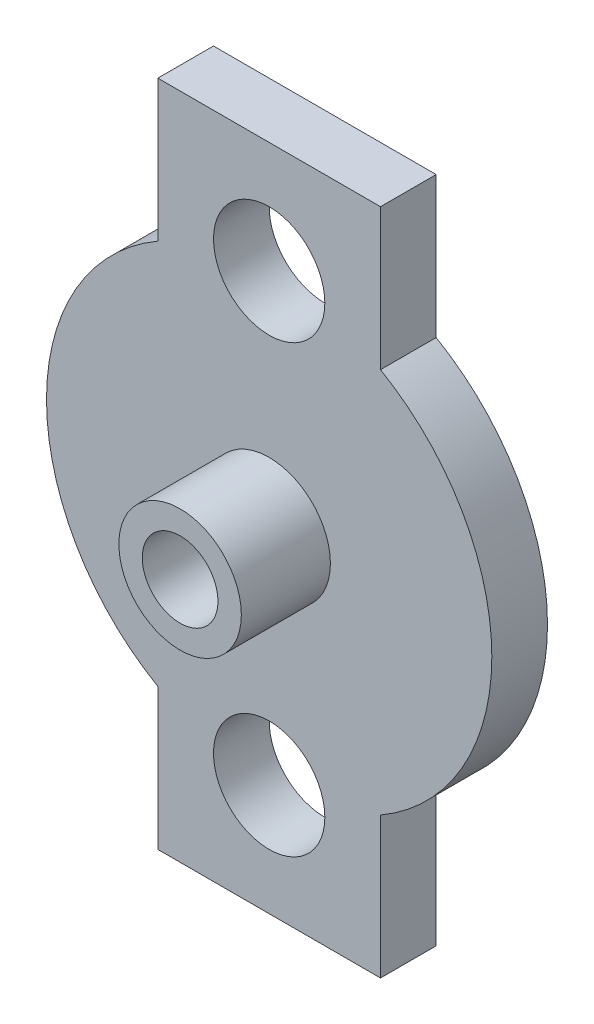
SolidWorks part; units mm, degrees
ref_plane "Plan de face" through (0, 0, 0) normal (0, 0, 1) x (1, 0, 0)
ref_plane "Plan de dessus" through (0, 0, 0) normal (0, 1, 0) x (1, 0, 0)
ref_plane "Plan de droite" through (0, 0, 0) normal (1, 0, 0) x (0, 0, -1)
sketch "Esquisse4" plane through (0, 0, 0) normal (0, 0, 1) x (1, 0, 0)
  circle A0 centre (0, 0) radius 10
  dimension "D1" = 20
extrude "Boss.-Extru.3" add sketch "Esquisse4" along normal blind 2.5
sketch "Esquisse5" plane through (0, 0, 2.5) normal (0, 0, 1) x (1, 0, 0)
  circle A0 centre (0, 0) radius 0.8
  dimension "D1" = 1.6
extrude "Enlèv. mat.-Extru.2" cut sketch "Esquisse5" against normal blind 3
sketch "Esquisse6" plane through (0, 0, 2.5) normal (0, 0, 1) x (1, 0, 0)
  circle A0 centre (0, 0) radius 1.7
  circle A1 centre (0, 0) radius 2.75
  dimension "D1" = 5.5
  dimension "D2" = 3.4
extrude "Boss.-Extru.4" add sketch "Esquisse6" along normal blind 4
sketch "Esquisse10" plane through (0, 0, 2.5) normal (0, 0, 1) x (1, 0, 0)
  circle A0 centre (0, 0) radius 1.7
  dimension "D1" = 3.4
extrude "Enlèv. mat.-Extru.3" cut sketch "Esquisse10" against normal blind 1
sketch "Esquisse17" plane through (0, 0, 2.5) normal (0, 0, 1) x (1, 0, 0)
  line L0 (-5, -8.6603) -> (-5, -15)
  line L1 (-5, -15) -> (5, -15)
  line L2 (5, -15) -> (5, -8.6603)
  line L4 (1.375, 0) -> (-1.375, 0) construction
  line L5 (5, 15) -> (5, 8.6603)
  line L6 (-5, 15) -> (5, 15)
  line L7 (-5, 8.6603) -> (-5, 15)
  circle A0 centre (0, 0) radius 10 construction
  arc A1 (-5, 8.6603) -> (5, 8.6603) centre (0, 0) cw
  circle A2 centre (0, 0) radius 10
  arc A3 (-5, -8.6603) -> (5, -8.6603) centre (0, 0) ccw
  dimension "D2" = 10
  dimension "D3" = 5
  dimension "D4" = 15
  dimension "D1" = 0
extrude "Boss.-Extru.8" add sketch "Esquisse17" against normal blind 2.5
sketch "Esquisse19" plane through (0, 0, 2.5) normal (0, 0, 1) x (1, 0, 0)
  line L0 (1.375, 0) -> (-1.375, 0) construction
  circle A0 centre (0, -10) radius 2.5
  circle A1 centre (0, 10) radius 2.5
  dimension "D1" = 5
  dimension "D2" = 10
  dimension "D3" = 0
extrude "Enlèv. mat.-Extru.4" cut sketch "Esquisse19" against normal blind 3
